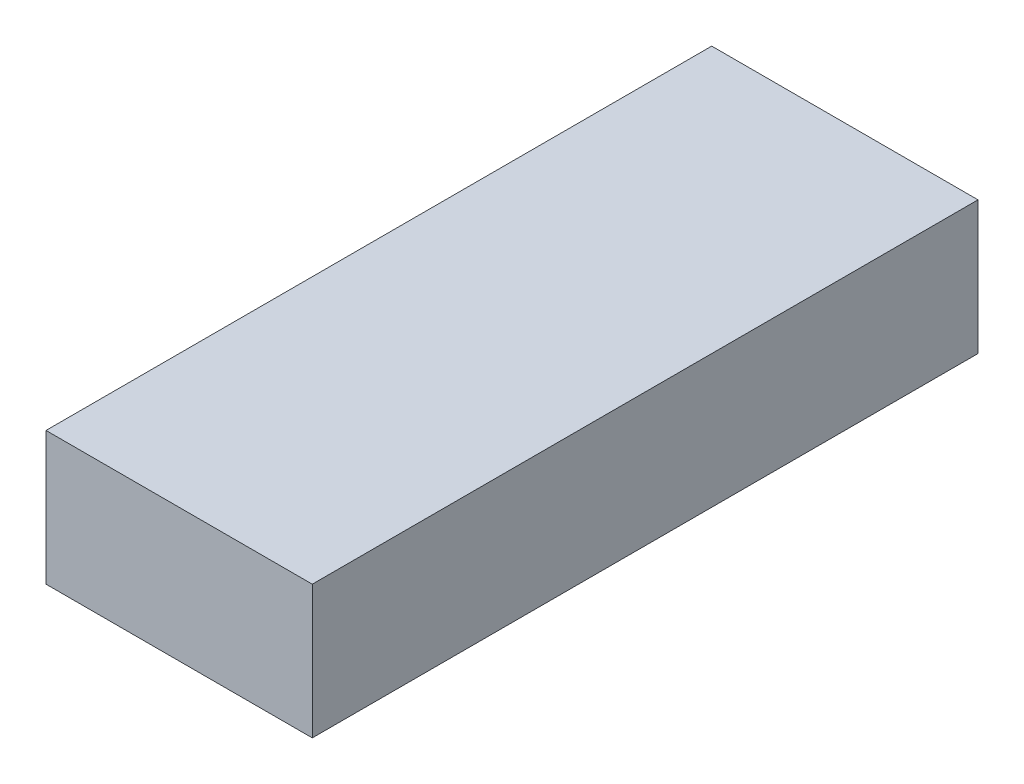
SolidWorks part; units mm, degrees
ref_plane "Front Plane" through (0, 0, 0) normal (0, 0, 1) x (1, 0, 0)
ref_plane "Top Plane" through (0, 0, 0) normal (0, 1, 0) x (1, 0, 0)
ref_plane "Right Plane" through (0, 0, 0) normal (1, 0, 0) x (0, 0, -1)
sketch "Sketch1" plane through (0, 0, 0) normal (0, 1, 0) x (1, 0, 0)
  line L0 (0, 0) -> (50.8, 0)
  line L1 (50.8, 0) -> (50.8, 127)
  line L2 (50.8, 127) -> (0, 127)
  line L3 (0, 127) -> (0, 0)
  dimension "D1" = 50.8
  dimension "D2" = 127
extrude "Boss-Extrude1" add sketch "Sketch1" along normal blind 25.4
